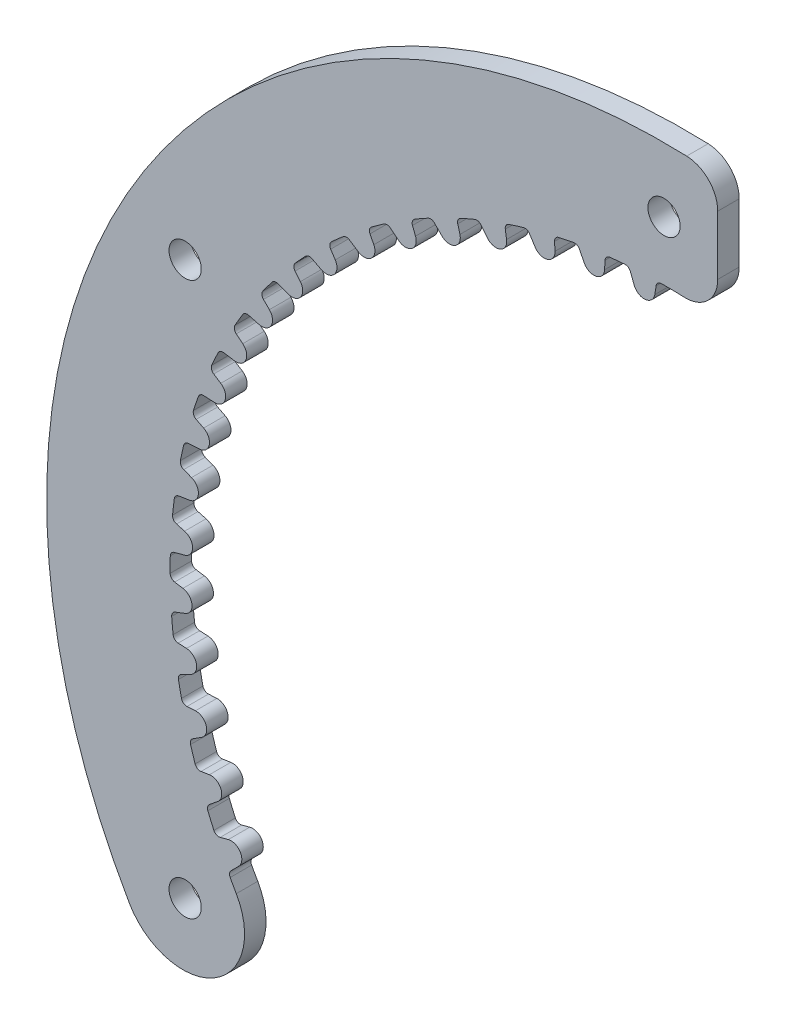
SolidWorks part; units mm, degrees
ref_plane "前视基准面" through (0, 0, 0) normal (0, 0, 1) x (1, 0, 0)
ref_plane "上视基准面" through (0, 0, 0) normal (0, 1, 0) x (1, 0, 0)
ref_plane "右视基准面" through (0, 0, 0) normal (1, 0, 0) x (0, 0, -1)
sketch "草图1" plane through (0, 0, 0) normal (0, 0, 1) x (1, 0, 0)
  line L6 (6.1601, 44.3885) -> (6.4016, 45.1318) [skipped]
  line L7 (0, 57.5) -> (6, 67.8923)
  line L10 (16.9119, 61.5923) -> (6.9151, 45.4773)
  line L11 (4.2309, 44.4896) -> (4.0233, 45.4665) [skipped]
  line L12 (3.8285, 44.65) -> (4.0308, 45.405)
  line L13 (1.8967, 44.65) -> (1.6382, 45.6147)
  line L14 (8.4748, 44.0052) -> (8.7549, 44.7349) [skipped]
  line L15 (6.5535, 44.2072) -> (6.3973, 45.1936) [skipped]
  line L16 (10.7662, 43.5014) -> (11.0841, 44.2154) [skipped]
  line L17 (8.8582, 43.8036) -> (8.7538, 44.7969) [skipped]
  line L164 (-37.109, -25.1238) -> (-37.823, -25.4417) [skipped]
  line L165 (-35.8932, -26.6252) -> (-36.4803, -27.4332) [skipped]
  line L166 (-38.373, -23.1473) -> (-39.1026, -23.4274) [skipped]
  line L167 (-37.2375, -24.7102) -> (-37.866, -25.4863) [skipped]
  line L168 (-39.5318, -21.1073) -> (-40.2752, -21.3488) [skipped]
  line L169 (-38.4797, -22.7274) -> (-39.148, -23.4697) [skipped]
  line L170 (-40.5823, -19.0094) -> (-41.3373, -19.2117)
  line L171 (-39.6164, -20.6824) -> (-40.3226, -21.3886)
  line L172 (-41.5216, -16.8594) -> (-42.2861, -17.0219) [skipped]
  line L173 (-40.6446, -18.5807) -> (-41.3868, -19.249) [skipped]
  line L174 (-42.347, -14.6633) -> (-43.119, -14.7855)
  line L175 (-41.5613, -16.4281) -> (-42.3375, -17.0566)
  line L176 (-43.0564, -12.4269) -> (-43.8337, -12.5086) [skipped]
  line L177 (-42.3641, -14.2304) -> (-43.1721, -14.8175) [skipped]
  line L178 (-43.6478, -10.1565) -> (-44.4283, -10.1974)
  line L179 (-43.0508, -11.9938) -> (-43.8884, -12.5377)
  line L180 (-44.1195, -7.8582) -> (-44.9011, -7.8582) [skipped]
  line L181 (-43.6195, -9.7242) -> (-44.4845, -10.2236) [skipped]
  line L182 (-44.4703, -5.5384) -> (-45.2508, -5.4975)
  line L183 (-44.0687, -7.428) -> (-44.9586, -7.8814)
  line L184 (-44.6992, -3.2034) -> (-45.4765, -3.1217) [skipped]
  line L185 (-44.397, -5.1115) -> (-45.3094, -5.5177) [skipped]
  line L186 (-44.8056, -0.8596) -> (-45.5776, -0.7374)
  line L187 (-44.6037, -2.7809) -> (-45.5361, -3.1388)
  line L188 (-44.7892, 1.4865) -> (-45.5537, 1.649) [skipped]
  line L189 (-44.6881, -0.4427) -> (-45.638, -0.7513) [skipped]
  line L190 (-44.65, 3.8285) -> (-45.405, 4.0308)
  line L191 (-44.65, 1.8967) -> (-45.6147, 1.6382)
  line L192 (-44.3885, 6.1601) -> (-45.1318, 6.4016) [skipped]
  line L193 (-44.4896, 4.2309) -> (-45.4665, 4.0233) [skipped]
  line L194 (-44.0052, 8.4748) -> (-44.7349, 8.7549)
  line L195 (-44.2072, 6.5535) -> (-45.1936, 6.3973)
  line L196 (-43.5014, 10.7662) -> (-44.2154, 11.0841) [skipped]
  line L197 (-43.8036, 8.8582) -> (-44.7969, 8.7538) [skipped]
  line L198 (-42.8783, 13.0282) -> (-43.5747, 13.383)
  line L199 (-43.28, 11.1385) -> (-44.2773, 11.0862)
  line L200 (-42.1377, 15.2544) -> (-42.8146, 15.6452) [skipped]
  line L201 (-42.6377, 13.3883) -> (-43.6365, 13.3883) [skipped]
  line L202 (-41.2816, 17.4388) -> (-41.9371, 17.8645)
  line L203 (-41.8786, 15.6015) -> (-42.876, 15.6538)
  line L204 (-40.3124, 19.5754) -> (-40.9447, 20.0348) [skipped]
  line L205 (-41.0047, 17.7719) -> (-41.9979, 17.8763) [skipped]
  line L206 (-39.2326, 21.6584) -> (-39.84, 22.1502)
  line L207 (-40.0184, 19.8935) -> (-41.0048, 20.0498)
  line L208 (-38.0454, 23.682) -> (-38.6262, 24.2049) [skipped]
  line L209 (-38.9224, 21.9607) -> (-39.8993, 22.1683) [skipped]
  line L210 (-36.7538, 25.6406) -> (-37.3064, 26.1933)
  line L211 (-37.7197, 23.9676) -> (-38.6844, 24.2261)
  line L212 (-35.3615, 27.529) -> (-35.8845, 28.1099) [skipped]
  line L213 (-36.4137, 25.9089) -> (-37.3635, 26.2175) [skipped]
  line L214 (-33.8723, 29.342) -> (-34.3641, 29.9494)
  line L215 (-35.0078, 27.7791) -> (-35.9402, 28.137)
  line L216 (-32.2902, 31.0745) -> (-32.7496, 31.7068) [skipped]
  line L217 (-33.506, 29.5732) -> (-34.4184, 29.9794) [skipped]
  line L218 (-30.6196, 32.7219) -> (-31.0453, 33.3773)
  line L219 (-31.9123, 31.2862) -> (-32.8022, 31.7396)
  line L220 (-28.8652, 34.2795) -> (-29.2559, 34.9564) [skipped]
  line L221 (-30.2312, 32.9135) -> (-31.0961, 33.4129) [skipped]
  line L222 (-27.0315, 35.7432) -> (-27.3864, 36.4396)
  line L223 (-28.4672, 34.4506) -> (-29.3048, 34.9945)
  line L224 (-25.1238, 37.109) -> (-25.4417, 37.823) [skipped]
  line L225 (-26.6252, 35.8932) -> (-27.4332, 36.4803) [skipped]
  line L226 (-23.1473, 38.373) -> (-23.4274, 39.1026)
  line L227 (-24.7102, 37.2375) -> (-25.4863, 37.866)
  line L228 (-21.1073, 39.5318) -> (-21.3488, 40.2752) [skipped]
  line L229 (-22.7274, 38.4797) -> (-23.4697, 39.148) [skipped]
  line L230 (-19.0094, 40.5823) -> (-19.2117, 41.3373)
  line L231 (-20.6824, 39.6164) -> (-21.3886, 40.3226)
  line L232 (-16.8594, 41.5216) -> (-17.0219, 42.2861) [skipped]
  line L233 (-18.5807, 40.6446) -> (-19.249, 41.3868) [skipped]
  line L234 (-14.6633, 42.347) -> (-14.7855, 43.119)
  line L235 (-16.4281, 41.5613) -> (-17.0566, 42.3375)
  line L236 (-12.4269, 43.0564) -> (-12.5086, 43.8337) [skipped]
  line L237 (-14.2304, 42.3641) -> (-14.8175, 43.1721) [skipped]
  line L238 (-10.1565, 43.6478) -> (-10.1974, 44.4283)
  line L239 (-11.9938, 43.0508) -> (-12.5377, 43.8884)
  line L240 (-7.8582, 44.1195) -> (-7.8582, 44.9011) [skipped]
  line L241 (-9.7242, 43.6195) -> (-10.2236, 44.4845) [skipped]
  line L242 (-5.5384, 44.4703) -> (-5.4975, 45.2508)
  line L243 (-7.428, 44.0687) -> (-7.8814, 44.9586)
  line L244 (-3.2034, 44.6992) -> (-3.1217, 45.4765) [skipped]
  line L245 (-5.1115, 44.397) -> (-5.5177, 45.3094) [skipped]
  line L246 (-0.8596, 44.8056) -> (-0.7374, 45.5776)
  line L247 (-2.7809, 44.6037) -> (-3.1388, 45.5361)
  line L248 (1.4865, 44.7892) -> (1.649, 45.5537) [skipped]
  line L249 (-0.4427, 44.6881) -> (-0.7513, 45.638) [skipped]
  line L250 (21.6584, 39.2326) -> (22.1502, 39.84) [skipped]
  line L251 (23.682, 38.0454) -> (24.2049, 38.6262) [skipped]
  line L252 (21.9607, 38.9224) -> (22.1683, 39.8993) [skipped]
  line L253 (25.6406, 36.7538) -> (26.1933, 37.3064) [skipped]
  line L254 (23.9676, 37.7197) -> (24.2261, 38.6844) [skipped]
  line L255 (27.529, 35.3615) -> (28.1099, 35.8845) [skipped]
  line L256 (25.9089, 36.4137) -> (26.2175, 37.3635) [skipped]
  line L257 (29.342, 33.8723) -> (29.9494, 34.3641) [skipped]
  line L258 (27.7791, 35.0078) -> (28.137, 35.9402) [skipped]
  line L259 (31.0745, 32.2902) -> (31.7068, 32.7496) [skipped]
  line L260 (29.5732, 33.506) -> (29.9794, 34.4184) [skipped]
  line L261 (32.7219, 30.6196) -> (33.3773, 31.0453) [skipped]
  line L262 (31.2862, 31.9123) -> (31.7396, 32.8022) [skipped]
  line L263 (34.2795, 28.8652) -> (34.9564, 29.2559) [skipped]
  line L264 (32.9135, 30.2312) -> (33.4129, 31.0961) [skipped]
  line L265 (35.7432, 27.0315) -> (36.4396, 27.3864) [skipped]
  line L266 (34.4506, 28.4672) -> (34.9945, 29.3048) [skipped]
  line L267 (37.109, 25.1238) -> (37.823, 25.4417) [skipped]
  line L268 (35.8932, 26.6252) -> (36.4803, 27.4332) [skipped]
  line L269 (38.373, 23.1473) -> (39.1026, 23.4274) [skipped]
  line L270 (37.2375, 24.7102) -> (37.866, 25.4863) [skipped]
  line L271 (39.5318, 21.1073) -> (40.2752, 21.3488) [skipped]
  line L272 (38.4797, 22.7274) -> (39.148, 23.4697) [skipped]
  line L273 (40.5823, 19.0094) -> (41.3373, 19.2117) [skipped]
  line L274 (39.6164, 20.6824) -> (40.3226, 21.3886) [skipped]
  line L275 (41.5216, 16.8594) -> (42.2861, 17.0219) [skipped]
  line L276 (40.6446, 18.5807) -> (41.3868, 19.249) [skipped]
  line L277 (42.347, 14.6633) -> (43.119, 14.7855) [skipped]
  line L278 (41.5613, 16.4281) -> (42.3375, 17.0566) [skipped]
  line L279 (43.0564, 12.4269) -> (43.8337, 12.5086) [skipped]
  line L280 (42.3641, 14.2304) -> (43.1721, 14.8175) [skipped]
  line L281 (43.6478, 10.1565) -> (44.4283, 10.1974) [skipped]
  line L282 (43.0508, 11.9938) -> (43.8884, 12.5377) [skipped]
  line L283 (44.1195, 7.8582) -> (44.9011, 7.8582) [skipped]
  line L284 (43.6195, 9.7242) -> (44.4845, 10.2236) [skipped]
  line L285 (44.4703, 5.5384) -> (45.2508, 5.4975) [skipped]
  line L286 (44.0687, 7.428) -> (44.9586, 7.8814) [skipped]
  line L287 (44.6992, 3.2034) -> (45.4765, 3.1217) [skipped]
  line L288 (44.397, 5.1115) -> (45.3094, 5.5177) [skipped]
  line L289 (44.8056, 0.8596) -> (45.5776, 0.7374) [skipped]
  line L290 (44.6037, 2.7809) -> (45.5361, 3.1388) [skipped]
  line L291 (44.7892, -1.4865) -> (45.5537, -1.649) [skipped]
  line L292 (44.6881, 0.4427) -> (45.638, 0.7513) [skipped]
  line L293 (44.65, -3.8285) -> (45.405, -4.0308) [skipped]
  line L294 (44.65, -1.8967) -> (45.6147, -1.6382) [skipped]
  line L295 (44.3885, -6.1601) -> (45.1318, -6.4016) [skipped]
  line L296 (44.4896, -4.2309) -> (45.4665, -4.0233) [skipped]
  line L297 (44.0052, -8.4748) -> (44.7349, -8.7549) [skipped]
  line L298 (44.2072, -6.5535) -> (45.1936, -6.3973) [skipped]
  line L299 (43.5014, -10.7662) -> (44.2154, -11.0841) [skipped]
  line L300 (43.8036, -8.8582) -> (44.7969, -8.7538) [skipped]
  line L301 (42.8783, -13.0282) -> (43.5747, -13.383) [skipped]
  line L302 (43.28, -11.1385) -> (44.2773, -11.0862) [skipped]
  line L303 (42.1377, -15.2544) -> (42.8146, -15.6452) [skipped]
  line L304 (42.6377, -13.3883) -> (43.6365, -13.3883) [skipped]
  line L305 (41.2816, -17.4388) -> (41.9371, -17.8645) [skipped]
  line L306 (41.8786, -15.6015) -> (42.876, -15.6538) [skipped]
  line L307 (40.3124, -19.5754) -> (40.9447, -20.0348) [skipped]
  line L308 (41.0047, -17.7719) -> (41.9979, -17.8763) [skipped]
  line L309 (39.2326, -21.6584) -> (39.84, -22.1502) [skipped]
  line L310 (40.0184, -19.8935) -> (41.0048, -20.0498) [skipped]
  line L311 (38.0454, -23.682) -> (38.6262, -24.2049) [skipped]
  line L312 (38.9224, -21.9607) -> (39.8993, -22.1683) [skipped]
  line L313 (36.7538, -25.6406) -> (37.3064, -26.1933) [skipped]
  line L314 (37.7197, -23.9676) -> (38.6844, -24.2261) [skipped]
  line L315 (35.3615, -27.529) -> (35.8845, -28.1099) [skipped]
  line L316 (36.4137, -25.9089) -> (37.3635, -26.2175) [skipped]
  line L317 (33.8723, -29.342) -> (34.3641, -29.9494) [skipped]
  line L318 (35.0078, -27.7791) -> (35.9402, -28.137) [skipped]
  line L319 (32.2902, -31.0745) -> (32.7496, -31.7068) [skipped]
  line L320 (33.506, -29.5732) -> (34.4184, -29.9794) [skipped]
  line L321 (30.6196, -32.7219) -> (31.0453, -33.3773) [skipped]
  line L322 (31.9123, -31.2862) -> (32.8022, -31.7396) [skipped]
  line L323 (28.8652, -34.2795) -> (29.2559, -34.9564) [skipped]
  line L324 (30.2312, -32.9135) -> (31.0961, -33.4129) [skipped]
  line L325 (27.0315, -35.7432) -> (27.3864, -36.4396) [skipped]
  line L326 (28.4672, -34.4506) -> (29.3048, -34.9945) [skipped]
  line L327 (25.1238, -37.109) -> (25.4417, -37.823) [skipped]
  line L328 (26.6252, -35.8932) -> (27.4332, -36.4803) [skipped]
  line L329 (23.1473, -38.373) -> (23.4274, -39.1026) [skipped]
  line L330 (24.7102, -37.2375) -> (25.4863, -37.866) [skipped]
  line L331 (21.1073, -39.5318) -> (21.3488, -40.2752) [skipped]
  line L332 (22.7274, -38.4797) -> (23.4697, -39.148) [skipped]
  line L333 (19.0094, -40.5823) -> (19.2117, -41.3373) [skipped]
  line L334 (20.6824, -39.6164) -> (21.3886, -40.3226) [skipped]
  line L335 (16.8594, -41.5216) -> (17.0219, -42.2861) [skipped]
  line L336 (18.5807, -40.6446) -> (19.249, -41.3868) [skipped]
  line L337 (14.6633, -42.347) -> (14.7855, -43.119) [skipped]
  line L338 (16.4281, -41.5613) -> (17.0566, -42.3375) [skipped]
  line L339 (12.4269, -43.0564) -> (12.5086, -43.8337) [skipped]
  line L340 (14.2304, -42.3641) -> (14.8175, -43.1721) [skipped]
  line L341 (10.1565, -43.6478) -> (10.1974, -44.4283) [skipped]
  line L342 (11.9938, -43.0508) -> (12.5377, -43.8884) [skipped]
  line L343 (7.8582, -44.1195) -> (7.8582, -44.9011) [skipped]
  line L344 (9.7242, -43.6195) -> (10.2236, -44.4845) [skipped]
  line L345 (5.5384, -44.4703) -> (5.4975, -45.2508) [skipped]
  line L346 (7.428, -44.0687) -> (7.8814, -44.9586) [skipped]
  line L347 (3.2034, -44.6992) -> (3.1217, -45.4765) [skipped]
  line L348 (5.1115, -44.397) -> (5.5177, -45.3094) [skipped]
  line L349 (0.8596, -44.8056) -> (0.7374, -45.5776) [skipped]
  line L350 (2.7809, -44.6037) -> (3.1388, -45.5361) [skipped]
  line L351 (-1.4865, -44.7892) -> (-1.649, -45.5537) [skipped]
  line L352 (0.4427, -44.6881) -> (0.7513, -45.638) [skipped]
  line L353 (-3.8285, -44.65) -> (-4.0308, -45.405) [skipped]
  line L354 (-1.8967, -44.65) -> (-1.6382, -45.6147) [skipped]
  line L355 (-6.1601, -44.3885) -> (-6.4016, -45.1318) [skipped]
  line L356 (-4.2309, -44.4896) -> (-4.0233, -45.4665) [skipped]
  line L357 (-8.4748, -44.0052) -> (-8.7549, -44.7349) [skipped]
  line L358 (-6.5535, -44.2072) -> (-6.3973, -45.1936) [skipped]
  line L359 (-10.7662, -43.5014) -> (-11.0841, -44.2154) [skipped]
  line L360 (-8.8582, -43.8036) -> (-8.7538, -44.7969) [skipped]
  line L361 (-13.0282, -42.8783) -> (-13.383, -43.5747) [skipped]
  line L362 (-11.1385, -43.28) -> (-11.0862, -44.2773) [skipped]
  line L363 (-15.2544, -42.1377) -> (-15.6452, -42.8146) [skipped]
  line L364 (-13.3883, -42.6377) -> (-13.3883, -43.6365) [skipped]
  line L365 (-17.4388, -41.2816) -> (-17.8645, -41.9371) [skipped]
  line L366 (-15.6015, -41.8786) -> (-15.6538, -42.876) [skipped]
  line L367 (-19.5754, -40.3124) -> (-20.0348, -40.9447) [skipped]
  line L368 (-17.7719, -41.0047) -> (-17.8763, -41.9979) [skipped]
  line L369 (-21.6584, -39.2326) -> (-22.1502, -39.84) [skipped]
  line L370 (-19.8935, -40.0184) -> (-20.0498, -41.0048) [skipped]
  line L371 (-23.682, -38.0454) -> (-24.2049, -38.6262) [skipped]
  line L372 (-21.9607, -38.9224) -> (-22.1683, -39.8993) [skipped]
  line L373 (-25.6406, -36.7538) -> (-26.1933, -37.3064) [skipped]
  line L374 (-23.9676, -37.7197) -> (-24.2261, -38.6844) [skipped]
  line L375 (-27.529, -35.3615) -> (-28.1099, -35.8845) [skipped]
  line L376 (-25.9089, -36.4137) -> (-26.2175, -37.3635) [skipped]
  line L377 (-29.342, -33.8723) -> (-29.9494, -34.3641) [skipped]
  line L378 (-27.7791, -35.0078) -> (-28.137, -35.9402) [skipped]
  line L379 (-31.0745, -32.2902) -> (-31.7068, -32.7496) [skipped]
  line L380 (-29.5732, -33.506) -> (-29.9794, -34.4184) [skipped]
  line L381 (-32.7219, -30.6196) -> (-33.3773, -31.0453) [skipped]
  line L382 (-31.2862, -31.9123) -> (-31.7396, -32.8022) [skipped]
  line L383 (-34.2795, -28.8652) -> (-34.9564, -29.2559) [skipped]
  line L384 (-32.9135, -30.2312) -> (-33.4129, -31.0961) [skipped]
  line L385 (-35.7432, -27.0315) -> (-36.4396, -27.3864) [skipped]
  line L386 (-34.4506, -28.4672) -> (-34.9945, -29.3048) [skipped]
  line L387 (13.0282, 42.8783) -> (13.383, 43.5747) [skipped]
  line L388 (11.1385, 43.28) -> (11.0862, 44.2773) [skipped]
  line L389 (15.2544, 42.1377) -> (15.6452, 42.8146) [skipped]
  line L390 (13.3883, 42.6377) -> (13.3883, 43.6365) [skipped]
  line L391 (17.4388, 41.2816) -> (17.8645, 41.9371) [skipped]
  line L392 (15.6015, 41.8786) -> (15.6538, 42.876) [skipped]
  line L393 (19.5754, 40.3124) -> (20.0348, 40.9447) [skipped]
  line L394 (17.7719, 41.0047) -> (17.8763, 41.9979) [skipped]
  line L395 (19.8935, 40.0184) -> (20.0498, 41.0048) [skipped]
  arc A0 (0, 57.5) -> (-49.7965, -28.75) centre (0, 0) ccw
  arc A2 (6.9151, 45.4773) -> (4.5634, 45.7731) centre (0, 0) ccw
  arc A3 (-49.7965, -28.75) -> (-39.8372, -23) centre (-44.8168, -25.875) ccw
  circle A4 centre (15.656, 72.0169) radius 3
  arc A5 (16.9119, 61.5923) -> (6, 67.8923) centre (15.656, 72.0169) ccw
  arc A12 (4.5634, 45.7731) -> (4.0308, 45.405) centre (4.5138, 45.2756) ccw
  arc A90 (1.8967, 44.65) -> (3.8285, 44.65) centre (2.8626, 44.9089) ccw
  arc A140 (1.6382, 45.6147) -> (1.1679, 45.9852) centre (1.1552, 45.4853) ccw
  arc A141 (4.2309, 44.4896) -> (6.1601, 44.3885) centre (5.209, 44.6975) ccw [skipped]
  arc A142 (6.9527, 45.4715) -> (6.4016, 45.1318) centre (6.8771, 44.9773) ccw [skipped]
  arc A143 (4.0233, 45.4665) -> (3.573, 45.861) centre (3.5342, 45.3625) ccw [skipped]
  arc A144 (6.5535, 44.2072) -> (8.4748, 44.0052) centre (7.5412, 44.3636) ccw [skipped]
  arc A145 (9.323, 45.0453) -> (8.7549, 44.7349) centre (9.2216, 44.5557) ccw [skipped]
  arc A146 (6.3973, 45.1936) -> (5.9683, 45.6112) centre (5.9034, 45.1154) ccw [skipped]
  arc A147 (8.8582, 43.8036) -> (10.7662, 43.5014) centre (9.8527, 43.9081) ccw [skipped]
  arc A148 (11.6677, 44.4957) -> (11.0841, 44.2154) centre (11.5409, 44.012) ccw [skipped]
  arc A149 (8.7538, 44.7969) -> (8.3472, 45.2363) centre (8.2565, 44.7446) ccw [skipped]
  arc A150 (-3.6452, 45.8553) -> (-5.0531, 45.7216) centre (0, 0) ccw
  arc A151 (1.1679, 45.9852) -> (-0.2462, 45.9993) centre (0, 0) ccw
  arc A152 (-8.4184, 45.2231) -> (-9.8046, 44.943) centre (0, 0) ccw
  arc A153 (-13.0994, 44.0954) -> (-14.4487, 43.6719) centre (0, 0) ccw
  arc A154 (-17.6369, 42.4846) -> (-18.9345, 41.9224) centre (0, 0) ccw
  arc A155 (-21.9811, 40.4083) -> (-23.2129, 39.7135) centre (0, 0) ccw
  arc A156 (-26.0845, 37.8893) -> (-27.2369, 37.0695) centre (0, 0) ccw
  arc A157 (-29.9021, 34.9551) -> (-30.9625, 34.0194) centre (0, 0) ccw
  arc A158 (-33.3921, 31.638) -> (-34.3489, 30.5966) centre (0, 0) ccw
  arc A159 (-36.5163, 27.9743) -> (-37.359, 26.8386) centre (0, 0) ccw
  arc A160 (-39.2404, 24.004) -> (-39.9597, 22.7865) centre (0, 0) ccw
  arc A161 (-41.5345, 19.7708) -> (-42.1226, 18.4847) centre (0, 0) ccw
  arc A162 (-43.3736, 15.321) -> (-43.8241, 13.9804) centre (0, 0) ccw
  arc A163 (-44.7375, 10.7033) -> (-45.0453, 9.323) centre (0, 0) ccw
  arc A164 (-45.6112, 5.9683) -> (-45.7731, 4.5634) centre (0, 0) ccw
  arc A165 (-45.9852, 1.1679) -> (-45.9993, -0.2462) centre (0, 0) ccw
  arc A166 (-45.8553, -3.6452) -> (-45.7216, -5.0531) centre (0, 0) ccw
  arc A167 (-45.2231, -8.4184) -> (-44.943, -9.8046) centre (0, 0) ccw
  arc A168 (-44.0954, -13.0994) -> (-43.6719, -14.4487) centre (0, 0) ccw
  arc A169 (-42.4846, -17.6369) -> (-41.9224, -18.9345) centre (0, 0) ccw
  arc A170 (-40.4083, -21.9811) -> (-39.8372, -23) centre (0, 0) ccw
  arc A369 (-35.8932, -26.6252) -> (-37.109, -25.1238) centre (-36.7022, -26.0374) ccw [skipped]
  arc A370 (-38.4442, -25.2595) -> (-37.823, -25.4417) centre (-38.0263, -24.985) ccw [skipped]
  arc A371 (-36.4803, -27.4332) -> (-36.4722, -28.0317) centre (-36.0758, -27.7271) ccw [skipped]
  arc A372 (-37.2375, -24.7102) -> (-38.373, -23.1473) centre (-38.0146, -24.0809) ccw [skipped]
  arc A373 (-39.7135, -23.2129) -> (-39.1026, -23.4274) centre (-39.2818, -22.9606) ccw [skipped]
  arc A374 (-37.866, -25.4863) -> (-37.8893, -26.0845) centre (-37.4774, -25.801) ccw [skipped]
  arc A375 (-38.4797, -22.7274) -> (-39.5318, -21.1073) centre (-39.2228, -22.0583) ccw [skipped]
  arc A376 (-40.8739, -21.1026) -> (-40.2752, -21.3488) centre (-40.4297, -20.8732) ccw [skipped]
  arc A377 (-39.148, -23.4697) -> (-39.2025, -24.0658) centre (-38.7764, -23.8042) ccw [skipped]
  arc A378 (-39.6164, -20.6824) -> (-40.5823, -19.0094) centre (-40.3235, -19.9753) ccw
  arc A379 (-41.9224, -18.9345) -> (-41.3373, -19.2117) centre (-41.4667, -18.7287) ccw
  arc A380 (-40.3226, -21.3886) -> (-40.4083, -21.9811) centre (-39.9691, -21.7422) ccw
  arc A381 (-40.6446, -18.5807) -> (-41.5216, -16.8594) centre (-41.3137, -17.8376) ccw [skipped]
  arc A382 (-42.8559, -16.7145) -> (-42.2861, -17.0219) centre (-42.39, -16.5329) ccw [skipped]
  arc A383 (-41.3868, -19.249) -> (-41.5033, -19.8362) centre (-41.0522, -19.6206) ccw [skipped]
  arc A384 (-41.5613, -16.4281) -> (-42.347, -14.6633) centre (-42.1906, -15.6509) ccw
  arc A385 (-43.6719, -14.4487) -> (-43.119, -14.7855) centre (-43.1972, -14.2917) ccw
  arc A386 (-42.3375, -17.0566) -> (-42.4846, -17.6369) centre (-42.0228, -17.4452) ccw
  arc A387 (-42.3641, -14.2304) -> (-43.0564, -12.4269) centre (-42.9519, -13.4214) ccw [skipped]
  arc A388 (-44.3682, -12.1433) -> (-43.8337, -12.5086) centre (-43.886, -12.0113) ccw [skipped]
  arc A389 (-43.1721, -14.8175) -> (-43.3494, -15.3892) centre (-42.8782, -15.222) ccw [skipped]
  arc A390 (-43.0508, -11.9938) -> (-43.6478, -10.1565) centre (-43.5955, -11.1551) ccw
  arc A391 (-44.943, -9.8046) -> (-44.4283, -10.1974) centre (-44.4544, -9.698) ccw
  arc A392 (-43.8884, -12.5377) -> (-44.0954, -13.0994) centre (-43.6161, -12.957) ccw
  arc A393 (-43.6195, -9.7242) -> (-44.1195, -7.8582) centre (-44.1195, -8.8582) ccw [skipped]
  arc A394 (-45.3945, -7.439) -> (-44.9011, -7.8582) centre (-44.9011, -7.3582) ccw [skipped]
  arc A395 (-44.4845, -10.2236) -> (-44.7205, -10.7737) centre (-44.2345, -10.6566) ccw [skipped]
  arc A396 (-44.0687, -7.428) -> (-44.4703, -5.5384) centre (-44.5227, -6.537) ccw
  arc A397 (-45.7216, -5.0531) -> (-45.2508, -5.4975) centre (-45.2246, -4.9982) ccw
  arc A398 (-44.9586, -7.8814) -> (-45.2231, -8.4184) centre (-44.7316, -8.3269) ccw
  arc A399 (-44.397, -5.1115) -> (-44.6992, -3.2034) centre (-44.8038, -4.1979) ccw [skipped]
  arc A400 (-45.9234, -2.6533) -> (-45.4765, -3.1217) centre (-45.4242, -2.6244) ccw [skipped]
  arc A401 (-45.3094, -5.5177) -> (-45.6017, -6.0401) centre (-45.1061, -5.9745) ccw [skipped]
  arc A402 (-44.6037, -2.7809) -> (-44.8056, -0.8596) centre (-44.9621, -1.8473) ccw
  arc A403 (-45.9993, -0.2462) -> (-45.5776, -0.7374) centre (-45.4993, -0.2435) ccw
  arc A404 (-45.5361, -3.1388) -> (-45.8553, -3.6452) centre (-45.3569, -3.6056) ccw
  arc A405 (-44.6881, -0.4427) -> (-44.7892, 1.4865) centre (-44.9971, 0.5084) ccw [skipped]
  arc A406 (-45.9492, 2.1616) -> (-45.5537, 1.649) centre (-45.4497, 2.1381) ccw [skipped]
  arc A407 (-45.638, -0.7513) -> (-45.9833, -1.2403) centre (-45.4835, -1.2269) ccw [skipped]
  arc A408 (-44.65, 1.8967) -> (-44.65, 3.8285) centre (-44.9089, 2.8626) ccw
  arc A409 (-45.7731, 4.5634) -> (-45.405, 4.0308) centre (-45.2756, 4.5138) ccw
  arc A410 (-45.6147, 1.6382) -> (-45.9852, 1.1679) centre (-45.4853, 1.1552) ccw
  arc A411 (-44.4896, 4.2309) -> (-44.3885, 6.1601) centre (-44.6975, 5.209) ccw [skipped]
  arc A412 (-45.4715, 6.9527) -> (-45.1318, 6.4016) centre (-44.9773, 6.8771) ccw [skipped]
  arc A413 (-45.4665, 4.0233) -> (-45.861, 3.573) centre (-45.3625, 3.5342) ccw [skipped]
  arc A414 (-44.2072, 6.5535) -> (-44.0052, 8.4748) centre (-44.3636, 7.5412) ccw
  arc A415 (-45.0453, 9.323) -> (-44.7349, 8.7549) centre (-44.5557, 9.2216) ccw
  arc A416 (-45.1936, 6.3973) -> (-45.6112, 5.9683) centre (-45.1154, 5.9034) ccw
  arc A417 (-43.8036, 8.8582) -> (-43.5014, 10.7662) centre (-43.9081, 9.8527) ccw [skipped]
  arc A418 (-44.4957, 11.6677) -> (-44.2154, 11.0841) centre (-44.012, 11.5409) ccw [skipped]
  arc A419 (-44.7969, 8.7538) -> (-45.2363, 8.3472) centre (-44.7446, 8.2565) ccw [skipped]
  arc A420 (-43.28, 11.1385) -> (-42.8783, 13.0282) centre (-43.3323, 12.1371) ccw
  arc A421 (-43.8241, 13.9804) -> (-43.5747, 13.383) centre (-43.3477, 13.8285) ccw
  arc A422 (-44.2773, 11.0862) -> (-44.7375, 10.7033) centre (-44.2512, 10.5869) ccw
  arc A423 (-42.6377, 13.3883) -> (-42.1377, 15.2544) centre (-42.6377, 14.3883) ccw [skipped]
  arc A424 (-43.0323, 16.2548) -> (-42.8146, 15.6452) centre (-42.5646, 16.0782) ccw [skipped]
  arc A425 (-43.6365, 13.3883) -> (-44.116, 13.03) centre (-43.6365, 12.8883) ccw [skipped]
  arc A426 (-41.8786, 15.6015) -> (-41.2816, 17.4388) centre (-41.8263, 16.6001) ccw
  arc A427 (-42.1226, 18.4847) -> (-41.9371, 17.8645) centre (-41.6648, 18.2838) ccw
  arc A428 (-42.876, 15.6538) -> (-43.3736, 15.321) centre (-42.9021, 15.1544) ccw
  arc A429 (-41.0047, 17.7719) -> (-40.3124, 19.5754) centre (-40.9002, 18.7664) ccw [skipped]
  arc A430 (-41.0975, 20.6639) -> (-40.9447, 20.0348) centre (-40.6508, 20.4393) ccw [skipped]
  arc A431 (-41.9979, 17.8763) -> (-42.5123, 17.57) centre (-42.0502, 17.379) ccw [skipped]
  arc A432 (-40.0184, 19.8935) -> (-39.2326, 21.6584) centre (-39.8619, 20.8812) ccw
  arc A433 (-39.9597, 22.7865) -> (-39.84, 22.1502) centre (-39.5254, 22.5388) ccw
  arc A434 (-41.0048, 20.0498) -> (-41.5345, 19.7708) centre (-41.083, 19.5559) ccw
  arc A435 (-38.9224, 21.9607) -> (-38.0454, 23.682) centre (-38.7145, 22.9388) ccw [skipped]
  arc A436 (-38.7124, 24.8466) -> (-38.6262, 24.2049) centre (-38.2916, 24.5765) ccw [skipped]
  arc A437 (-39.8993, 22.1683) -> (-40.4429, 21.9175) centre (-40.0033, 21.6792) ccw [skipped]
  arc A438 (-37.7197, 23.9676) -> (-36.7538, 25.6406) centre (-37.4609, 24.9335) ccw
  arc A439 (-37.359, 26.8386) -> (-37.3064, 26.1933) centre (-36.9529, 26.5468) ccw
  arc A440 (-38.6844, 24.2261) -> (-39.2404, 24.004) centre (-38.8138, 23.7431) ccw
  arc A441 (-36.4137, 25.9089) -> (-35.3615, 27.529) centre (-36.1046, 26.8599) ccw [skipped]
  arc A442 (-35.9031, 28.757) -> (-35.8845, 28.1099) centre (-35.5129, 28.4444) ccw [skipped]
  arc A443 (-37.3635, 26.2175) -> (-37.9303, 26.0248) centre (-37.518, 25.742) ccw [skipped]
  arc A444 (-35.0078, 27.7791) -> (-33.8723, 29.342) centre (-34.6494, 28.7127) ccw
  arc A445 (-34.3489, 30.5966) -> (-34.3641, 29.9494) centre (-33.9756, 30.264) ccw
  arc A446 (-35.9402, 28.137) -> (-36.5163, 27.9743) centre (-36.1194, 27.6702) ccw
  arc A447 (-33.506, 29.5732) -> (-32.2902, 31.0745) centre (-33.0992, 30.4867) ccw [skipped]
  arc A448 (-32.7005, 32.3524) -> (-32.7496, 31.7068) centre (-32.3451, 32.0007) ccw [skipped]
  arc A449 (-34.4184, 29.9794) -> (-35.0022, 29.8471) centre (-34.6217, 29.5226) ccw [skipped]
  arc A450 (-31.9123, 31.2862) -> (-30.6196, 32.7219) centre (-31.4583, 32.1772) ccw
  arc A451 (-30.9625, 34.0194) -> (-31.0453, 33.3773) centre (-30.626, 33.6497) ccw
  arc A452 (-32.8022, 31.7396) -> (-33.3921, 31.638) centre (-33.0292, 31.2941) ccw
  arc A453 (-30.2312, 32.9135) -> (-28.8652, 34.2795) centre (-29.7312, 33.7795) ccw [skipped]
  arc A454 (-29.1397, 35.5933) -> (-29.2559, 34.9564) centre (-28.8229, 35.2064) ccw [skipped]
  arc A455 (-31.0961, 33.4129) -> (-31.6906, 33.3423) centre (-31.3461, 32.9799) ccw [skipped]
  arc A456 (-28.4672, 34.4506) -> (-27.0315, 35.7432) centre (-27.9225, 35.2893) ccw
  arc A457 (-27.2369, 37.0695) -> (-27.3864, 36.4396) centre (-26.9409, 36.6666) ccw
  arc A458 (-29.3048, 34.9945) -> (-29.9021, 34.9551) centre (-29.5771, 34.5752) ccw
  arc A459 (-26.6252, 35.8932) -> (-25.1238, 37.109) centre (-26.0374, 36.7022) ccw [skipped]
  arc A460 (-25.2595, 38.4442) -> (-25.4417, 37.823) centre (-24.985, 38.0263) ccw [skipped]
  arc A461 (-27.4332, 36.4803) -> (-28.0317, 36.4722) centre (-27.7271, 36.0758) ccw [skipped]
  arc A462 (-24.7102, 37.2375) -> (-23.1473, 38.373) centre (-24.0809, 38.0146) ccw
  arc A463 (-23.2129, 39.7135) -> (-23.4274, 39.1026) centre (-22.9606, 39.2818) ccw
  arc A464 (-25.4863, 37.866) -> (-26.0845, 37.8893) centre (-25.801, 37.4774) ccw
  arc A465 (-22.7274, 38.4797) -> (-21.1073, 39.5318) centre (-22.0583, 39.2228) ccw [skipped]
  arc A466 (-21.1026, 40.8739) -> (-21.3488, 40.2752) centre (-20.8732, 40.4297) ccw [skipped]
  arc A467 (-23.4697, 39.148) -> (-24.0658, 39.2025) centre (-23.8042, 38.7764) ccw [skipped]
  arc A468 (-20.6824, 39.6164) -> (-19.0094, 40.5823) centre (-19.9753, 40.3235) ccw
  arc A469 (-18.9345, 41.9224) -> (-19.2117, 41.3373) centre (-18.7287, 41.4667) ccw
  arc A470 (-21.3886, 40.3226) -> (-21.9811, 40.4083) centre (-21.7422, 39.9691) ccw
  arc A471 (-18.5807, 40.6446) -> (-16.8594, 41.5216) centre (-17.8376, 41.3137) ccw [skipped]
  arc A472 (-16.7145, 42.8559) -> (-17.0219, 42.2861) centre (-16.5329, 42.39) ccw [skipped]
  arc A473 (-19.249, 41.3868) -> (-19.8362, 41.5033) centre (-19.6206, 41.0522) ccw [skipped]
  arc A474 (-16.4281, 41.5613) -> (-14.6633, 42.347) centre (-15.6509, 42.1906) ccw
  arc A475 (-14.4487, 43.6719) -> (-14.7855, 43.119) centre (-14.2917, 43.1972) ccw
  arc A476 (-17.0566, 42.3375) -> (-17.6369, 42.4846) centre (-17.4452, 42.0228) ccw
  arc A477 (-14.2304, 42.3641) -> (-12.4269, 43.0564) centre (-13.4214, 42.9519) ccw [skipped]
  arc A478 (-12.1433, 44.3682) -> (-12.5086, 43.8337) centre (-12.0113, 43.886) ccw [skipped]
  arc A479 (-14.8175, 43.1721) -> (-15.3892, 43.3494) centre (-15.222, 42.8782) ccw [skipped]
  arc A480 (-11.9938, 43.0508) -> (-10.1565, 43.6478) centre (-11.1551, 43.5955) ccw
  arc A481 (-9.8046, 44.943) -> (-10.1974, 44.4283) centre (-9.698, 44.4544) ccw
  arc A482 (-12.5377, 43.8884) -> (-13.0994, 44.0954) centre (-12.957, 43.6161) ccw
  arc A483 (-9.7242, 43.6195) -> (-7.8582, 44.1195) centre (-8.8582, 44.1195) ccw [skipped]
  arc A484 (-7.439, 45.3945) -> (-7.8582, 44.9011) centre (-7.3582, 44.9011) ccw [skipped]
  arc A485 (-10.2236, 44.4845) -> (-10.7737, 44.7205) centre (-10.6566, 44.2345) ccw [skipped]
  arc A486 (-7.428, 44.0687) -> (-5.5384, 44.4703) centre (-6.537, 44.5227) ccw
  arc A487 (-5.0531, 45.7216) -> (-5.4975, 45.2508) centre (-4.9982, 45.2246) ccw
  arc A488 (-7.8814, 44.9586) -> (-8.4184, 45.2231) centre (-8.3269, 44.7316) ccw
  arc A489 (-5.1115, 44.397) -> (-3.2034, 44.6992) centre (-4.1979, 44.8038) ccw [skipped]
  arc A490 (-2.6533, 45.9234) -> (-3.1217, 45.4765) centre (-2.6244, 45.4242) ccw [skipped]
  arc A491 (-5.5177, 45.3094) -> (-6.0401, 45.6017) centre (-5.9745, 45.1061) ccw [skipped]
  arc A492 (-2.7809, 44.6037) -> (-0.8596, 44.8056) centre (-1.8473, 44.9621) ccw
  arc A493 (-0.2462, 45.9993) -> (-0.7374, 45.5776) centre (-0.2435, 45.4993) ccw
  arc A494 (-3.1388, 45.5361) -> (-3.6452, 45.8553) centre (-3.6056, 45.3569) ccw
  arc A495 (-0.4427, 44.6881) -> (1.4865, 44.7892) centre (0.5084, 44.9971) ccw [skipped]
  arc A496 (2.1616, 45.9492) -> (1.649, 45.5537) centre (2.1381, 45.4497) ccw [skipped]
  arc A497 (-0.7513, 45.638) -> (-1.2403, 45.9833) centre (-1.2269, 45.4835) ccw [skipped]
  arc A498 (19.8935, 40.0184) -> (21.6584, 39.2326) centre (20.8812, 39.8619) ccw [skipped]
  arc A499 (22.7865, 39.9597) -> (22.1502, 39.84) centre (22.5388, 39.5254) ccw [skipped]
  arc A500 (21.9607, 38.9224) -> (23.682, 38.0454) centre (22.9388, 38.7145) ccw [skipped]
  arc A501 (24.8466, 38.7124) -> (24.2049, 38.6262) centre (24.5765, 38.2916) ccw [skipped]
  arc A502 (22.1683, 39.8993) -> (21.9175, 40.4429) centre (21.6792, 40.0033) ccw [skipped]
  arc A503 (23.9676, 37.7197) -> (25.6406, 36.7538) centre (24.9335, 37.4609) ccw [skipped]
  arc A504 (26.8386, 37.359) -> (26.1933, 37.3064) centre (26.5468, 36.9529) ccw [skipped]
  arc A505 (24.2261, 38.6844) -> (24.004, 39.2404) centre (23.7431, 38.8138) ccw [skipped]
  arc A506 (25.9089, 36.4137) -> (27.529, 35.3615) centre (26.8599, 36.1046) ccw [skipped]
  arc A507 (28.757, 35.9031) -> (28.1099, 35.8845) centre (28.4444, 35.5129) ccw [skipped]
  arc A508 (26.2175, 37.3635) -> (26.0248, 37.9303) centre (25.742, 37.518) ccw [skipped]
  arc A509 (27.7791, 35.0078) -> (29.342, 33.8723) centre (28.7127, 34.6494) ccw [skipped]
  arc A510 (30.5966, 34.3489) -> (29.9494, 34.3641) centre (30.264, 33.9756) ccw [skipped]
  arc A511 (28.137, 35.9402) -> (27.9743, 36.5163) centre (27.6702, 36.1194) ccw [skipped]
  arc A512 (29.5732, 33.506) -> (31.0745, 32.2902) centre (30.4867, 33.0992) ccw [skipped]
  arc A513 (32.3524, 32.7005) -> (31.7068, 32.7496) centre (32.0007, 32.3451) ccw [skipped]
  arc A514 (29.9794, 34.4184) -> (29.8471, 35.0022) centre (29.5226, 34.6217) ccw [skipped]
  arc A515 (31.2862, 31.9123) -> (32.7219, 30.6196) centre (32.1772, 31.4583) ccw [skipped]
  arc A516 (34.0194, 30.9625) -> (33.3773, 31.0453) centre (33.6497, 30.626) ccw [skipped]
  arc A517 (31.7396, 32.8022) -> (31.638, 33.3921) centre (31.2941, 33.0292) ccw [skipped]
  arc A518 (32.9135, 30.2312) -> (34.2795, 28.8652) centre (33.7795, 29.7312) ccw [skipped]
  arc A519 (35.5933, 29.1397) -> (34.9564, 29.2559) centre (35.2064, 28.8229) ccw [skipped]
  arc A520 (33.4129, 31.0961) -> (33.3423, 31.6906) centre (32.9799, 31.3461) ccw [skipped]
  arc A521 (34.4506, 28.4672) -> (35.7432, 27.0315) centre (35.2893, 27.9225) ccw [skipped]
  arc A522 (37.0695, 27.2369) -> (36.4396, 27.3864) centre (36.6666, 26.9409) ccw [skipped]
  arc A523 (34.9945, 29.3048) -> (34.9551, 29.9021) centre (34.5752, 29.5771) ccw [skipped]
  arc A524 (35.8932, 26.6252) -> (37.109, 25.1238) centre (36.7022, 26.0374) ccw [skipped]
  arc A525 (38.4442, 25.2595) -> (37.823, 25.4417) centre (38.0263, 24.985) ccw [skipped]
  arc A526 (36.4803, 27.4332) -> (36.4722, 28.0317) centre (36.0758, 27.7271) ccw [skipped]
  arc A527 (37.2375, 24.7102) -> (38.373, 23.1473) centre (38.0146, 24.0809) ccw [skipped]
  arc A528 (39.7135, 23.2129) -> (39.1026, 23.4274) centre (39.2818, 22.9606) ccw [skipped]
  arc A529 (37.866, 25.4863) -> (37.8893, 26.0845) centre (37.4774, 25.801) ccw [skipped]
  arc A530 (38.4797, 22.7274) -> (39.5318, 21.1073) centre (39.2228, 22.0583) ccw [skipped]
  arc A531 (40.8739, 21.1026) -> (40.2752, 21.3488) centre (40.4297, 20.8732) ccw [skipped]
  arc A532 (39.148, 23.4697) -> (39.2025, 24.0658) centre (38.7764, 23.8042) ccw [skipped]
  arc A533 (39.6164, 20.6824) -> (40.5823, 19.0094) centre (40.3235, 19.9753) ccw [skipped]
  arc A534 (41.9224, 18.9345) -> (41.3373, 19.2117) centre (41.4667, 18.7287) ccw [skipped]
  arc A535 (40.3226, 21.3886) -> (40.4083, 21.9811) centre (39.9691, 21.7422) ccw [skipped]
  arc A536 (40.6446, 18.5807) -> (41.5216, 16.8594) centre (41.3137, 17.8376) ccw [skipped]
  arc A537 (42.8559, 16.7145) -> (42.2861, 17.0219) centre (42.39, 16.5329) ccw [skipped]
  arc A538 (41.3868, 19.249) -> (41.5033, 19.8362) centre (41.0522, 19.6206) ccw [skipped]
  arc A539 (41.5613, 16.4281) -> (42.347, 14.6633) centre (42.1906, 15.6509) ccw [skipped]
  arc A540 (43.6719, 14.4487) -> (43.119, 14.7855) centre (43.1972, 14.2917) ccw [skipped]
  arc A541 (42.3375, 17.0566) -> (42.4846, 17.6369) centre (42.0228, 17.4452) ccw [skipped]
  arc A542 (42.3641, 14.2304) -> (43.0564, 12.4269) centre (42.9519, 13.4214) ccw [skipped]
  arc A543 (44.3682, 12.1433) -> (43.8337, 12.5086) centre (43.886, 12.0113) ccw [skipped]
  arc A544 (43.1721, 14.8175) -> (43.3494, 15.3892) centre (42.8782, 15.222) ccw [skipped]
  arc A545 (43.0508, 11.9938) -> (43.6478, 10.1565) centre (43.5955, 11.1551) ccw [skipped]
  arc A546 (44.943, 9.8046) -> (44.4283, 10.1974) centre (44.4544, 9.698) ccw [skipped]
  arc A547 (43.8884, 12.5377) -> (44.0954, 13.0994) centre (43.6161, 12.957) ccw [skipped]
  arc A548 (43.6195, 9.7242) -> (44.1195, 7.8582) centre (44.1195, 8.8582) ccw [skipped]
  arc A549 (45.3945, 7.439) -> (44.9011, 7.8582) centre (44.9011, 7.3582) ccw [skipped]
  arc A550 (44.4845, 10.2236) -> (44.7205, 10.7737) centre (44.2345, 10.6566) ccw [skipped]
  arc A551 (44.0687, 7.428) -> (44.4703, 5.5384) centre (44.5227, 6.537) ccw [skipped]
  arc A552 (45.7216, 5.0531) -> (45.2508, 5.4975) centre (45.2246, 4.9982) ccw [skipped]
  arc A553 (44.9586, 7.8814) -> (45.2231, 8.4184) centre (44.7316, 8.3269) ccw [skipped]
  arc A554 (44.397, 5.1115) -> (44.6992, 3.2034) centre (44.8038, 4.1979) ccw [skipped]
  arc A555 (45.9234, 2.6533) -> (45.4765, 3.1217) centre (45.4242, 2.6244) ccw [skipped]
  arc A556 (45.3094, 5.5177) -> (45.6017, 6.0401) centre (45.1061, 5.9745) ccw [skipped]
  arc A557 (44.6037, 2.7809) -> (44.8056, 0.8596) centre (44.9621, 1.8473) ccw [skipped]
  arc A558 (45.9993, 0.2462) -> (45.5776, 0.7374) centre (45.4993, 0.2435) ccw [skipped]
  arc A559 (45.5361, 3.1388) -> (45.8553, 3.6452) centre (45.3569, 3.6056) ccw [skipped]
  arc A560 (44.6881, 0.4427) -> (44.7892, -1.4865) centre (44.9971, -0.5084) ccw [skipped]
  arc A561 (45.9492, -2.1616) -> (45.5537, -1.649) centre (45.4497, -2.1381) ccw [skipped]
  arc A562 (45.638, 0.7513) -> (45.9833, 1.2403) centre (45.4835, 1.2269) ccw [skipped]
  arc A563 (44.65, -1.8967) -> (44.65, -3.8285) centre (44.9089, -2.8626) ccw [skipped]
  arc A564 (45.7731, -4.5634) -> (45.405, -4.0308) centre (45.2756, -4.5138) ccw [skipped]
  arc A565 (45.6147, -1.6382) -> (45.9852, -1.1679) centre (45.4853, -1.1552) ccw [skipped]
  arc A566 (44.4896, -4.2309) -> (44.3885, -6.1601) centre (44.6975, -5.209) ccw [skipped]
  arc A567 (45.4715, -6.9527) -> (45.1318, -6.4016) centre (44.9773, -6.8771) ccw [skipped]
  arc A568 (45.4665, -4.0233) -> (45.861, -3.573) centre (45.3625, -3.5342) ccw [skipped]
  arc A569 (44.2072, -6.5535) -> (44.0052, -8.4748) centre (44.3636, -7.5412) ccw [skipped]
  arc A570 (45.0453, -9.323) -> (44.7349, -8.7549) centre (44.5557, -9.2216) ccw [skipped]
  arc A571 (45.1936, -6.3973) -> (45.6112, -5.9683) centre (45.1154, -5.9034) ccw [skipped]
  arc A572 (43.8036, -8.8582) -> (43.5014, -10.7662) centre (43.9081, -9.8527) ccw [skipped]
  arc A573 (44.4957, -11.6677) -> (44.2154, -11.0841) centre (44.012, -11.5409) ccw [skipped]
  arc A574 (44.7969, -8.7538) -> (45.2363, -8.3472) centre (44.7446, -8.2565) ccw [skipped]
  arc A575 (43.28, -11.1385) -> (42.8783, -13.0282) centre (43.3323, -12.1371) ccw [skipped]
  arc A576 (43.8241, -13.9804) -> (43.5747, -13.383) centre (43.3477, -13.8285) ccw [skipped]
  arc A577 (44.2773, -11.0862) -> (44.7375, -10.7033) centre (44.2512, -10.5869) ccw [skipped]
  arc A578 (42.6377, -13.3883) -> (42.1377, -15.2544) centre (42.6377, -14.3883) ccw [skipped]
  arc A579 (43.0323, -16.2548) -> (42.8146, -15.6452) centre (42.5646, -16.0782) ccw [skipped]
  arc A580 (43.6365, -13.3883) -> (44.116, -13.03) centre (43.6365, -12.8883) ccw [skipped]
  arc A581 (41.8786, -15.6015) -> (41.2816, -17.4388) centre (41.8263, -16.6001) ccw [skipped]
  arc A582 (42.1226, -18.4847) -> (41.9371, -17.8645) centre (41.6648, -18.2838) ccw [skipped]
  arc A583 (42.876, -15.6538) -> (43.3736, -15.321) centre (42.9021, -15.1544) ccw [skipped]
  arc A584 (41.0047, -17.7719) -> (40.3124, -19.5754) centre (40.9002, -18.7664) ccw [skipped]
  arc A585 (41.0975, -20.6639) -> (40.9447, -20.0348) centre (40.6508, -20.4393) ccw [skipped]
  arc A586 (41.9979, -17.8763) -> (42.5123, -17.57) centre (42.0502, -17.379) ccw [skipped]
  arc A587 (40.0184, -19.8935) -> (39.2326, -21.6584) centre (39.8619, -20.8812) ccw [skipped]
  arc A588 (39.9597, -22.7865) -> (39.84, -22.1502) centre (39.5254, -22.5388) ccw [skipped]
  arc A589 (41.0048, -20.0498) -> (41.5345, -19.7708) centre (41.083, -19.5559) ccw [skipped]
  arc A590 (38.9224, -21.9607) -> (38.0454, -23.682) centre (38.7145, -22.9388) ccw [skipped]
  arc A591 (38.7124, -24.8466) -> (38.6262, -24.2049) centre (38.2916, -24.5765) ccw [skipped]
  arc A592 (39.8993, -22.1683) -> (40.4429, -21.9175) centre (40.0033, -21.6792) ccw [skipped]
  arc A593 (37.7197, -23.9676) -> (36.7538, -25.6406) centre (37.4609, -24.9335) ccw [skipped]
  arc A594 (37.359, -26.8386) -> (37.3064, -26.1933) centre (36.9529, -26.5468) ccw [skipped]
  arc A595 (38.6844, -24.2261) -> (39.2404, -24.004) centre (38.8138, -23.7431) ccw [skipped]
  arc A596 (36.4137, -25.9089) -> (35.3615, -27.529) centre (36.1046, -26.8599) ccw [skipped]
  arc A597 (35.9031, -28.757) -> (35.8845, -28.1099) centre (35.5129, -28.4444) ccw [skipped]
  arc A598 (37.3635, -26.2175) -> (37.9303, -26.0248) centre (37.518, -25.742) ccw [skipped]
  arc A599 (35.0078, -27.7791) -> (33.8723, -29.342) centre (34.6494, -28.7127) ccw [skipped]
  arc A600 (34.3489, -30.5966) -> (34.3641, -29.9494) centre (33.9756, -30.264) ccw [skipped]
  arc A601 (35.9402, -28.137) -> (36.5163, -27.9743) centre (36.1194, -27.6702) ccw [skipped]
  arc A602 (33.506, -29.5732) -> (32.2902, -31.0745) centre (33.0992, -30.4867) ccw [skipped]
  arc A603 (32.7005, -32.3524) -> (32.7496, -31.7068) centre (32.3451, -32.0007) ccw [skipped]
  arc A604 (34.4184, -29.9794) -> (35.0022, -29.8471) centre (34.6217, -29.5226) ccw [skipped]
  arc A605 (31.9123, -31.2862) -> (30.6196, -32.7219) centre (31.4583, -32.1772) ccw [skipped]
  arc A606 (30.9625, -34.0194) -> (31.0453, -33.3773) centre (30.626, -33.6497) ccw [skipped]
  arc A607 (32.8022, -31.7396) -> (33.3921, -31.638) centre (33.0292, -31.2941) ccw [skipped]
  arc A608 (30.2312, -32.9135) -> (28.8652, -34.2795) centre (29.7312, -33.7795) ccw [skipped]
  arc A609 (29.1397, -35.5933) -> (29.2559, -34.9564) centre (28.8229, -35.2064) ccw [skipped]
  arc A610 (31.0961, -33.4129) -> (31.6906, -33.3423) centre (31.3461, -32.9799) ccw [skipped]
  arc A611 (28.4672, -34.4506) -> (27.0315, -35.7432) centre (27.9225, -35.2893) ccw [skipped]
  arc A612 (27.2369, -37.0695) -> (27.3864, -36.4396) centre (26.9409, -36.6666) ccw [skipped]
  arc A613 (29.3048, -34.9945) -> (29.9021, -34.9551) centre (29.5771, -34.5752) ccw [skipped]
  arc A614 (26.6252, -35.8932) -> (25.1238, -37.109) centre (26.0374, -36.7022) ccw [skipped]
  arc A615 (25.2595, -38.4442) -> (25.4417, -37.823) centre (24.985, -38.0263) ccw [skipped]
  arc A616 (27.4332, -36.4803) -> (28.0317, -36.4722) centre (27.7271, -36.0758) ccw [skipped]
  arc A617 (24.7102, -37.2375) -> (23.1473, -38.373) centre (24.0809, -38.0146) ccw [skipped]
  arc A618 (23.2129, -39.7135) -> (23.4274, -39.1026) centre (22.9606, -39.2818) ccw [skipped]
  arc A619 (25.4863, -37.866) -> (26.0845, -37.8893) centre (25.801, -37.4774) ccw [skipped]
  arc A620 (22.7274, -38.4797) -> (21.1073, -39.5318) centre (22.0583, -39.2228) ccw [skipped]
  arc A621 (21.1026, -40.8739) -> (21.3488, -40.2752) centre (20.8732, -40.4297) ccw [skipped]
  arc A622 (23.4697, -39.148) -> (24.0658, -39.2025) centre (23.8042, -38.7764) ccw [skipped]
  arc A623 (20.6824, -39.6164) -> (19.0094, -40.5823) centre (19.9753, -40.3235) ccw [skipped]
  arc A624 (18.9345, -41.9224) -> (19.2117, -41.3373) centre (18.7287, -41.4667) ccw [skipped]
  arc A625 (21.3886, -40.3226) -> (21.9811, -40.4083) centre (21.7422, -39.9691) ccw [skipped]
  arc A626 (18.5807, -40.6446) -> (16.8594, -41.5216) centre (17.8376, -41.3137) ccw [skipped]
  arc A627 (16.7145, -42.8559) -> (17.0219, -42.2861) centre (16.5329, -42.39) ccw [skipped]
  arc A628 (19.249, -41.3868) -> (19.8362, -41.5033) centre (19.6206, -41.0522) ccw [skipped]
  arc A629 (16.4281, -41.5613) -> (14.6633, -42.347) centre (15.6509, -42.1906) ccw [skipped]
  arc A630 (14.4487, -43.6719) -> (14.7855, -43.119) centre (14.2917, -43.1972) ccw [skipped]
  arc A631 (17.0566, -42.3375) -> (17.6369, -42.4846) centre (17.4452, -42.0228) ccw [skipped]
  arc A632 (14.2304, -42.3641) -> (12.4269, -43.0564) centre (13.4214, -42.9519) ccw [skipped]
  arc A633 (12.1433, -44.3682) -> (12.5086, -43.8337) centre (12.0113, -43.886) ccw [skipped]
  arc A634 (14.8175, -43.1721) -> (15.3892, -43.3494) centre (15.222, -42.8782) ccw [skipped]
  arc A635 (11.9938, -43.0508) -> (10.1565, -43.6478) centre (11.1551, -43.5955) ccw [skipped]
  arc A636 (9.8046, -44.943) -> (10.1974, -44.4283) centre (9.698, -44.4544) ccw [skipped]
  arc A637 (12.5377, -43.8884) -> (13.0994, -44.0954) centre (12.957, -43.6161) ccw [skipped]
  arc A638 (9.7242, -43.6195) -> (7.8582, -44.1195) centre (8.8582, -44.1195) ccw [skipped]
  arc A639 (7.439, -45.3945) -> (7.8582, -44.9011) centre (7.3582, -44.9011) ccw [skipped]
  arc A640 (10.2236, -44.4845) -> (10.7737, -44.7205) centre (10.6566, -44.2345) ccw [skipped]
  arc A641 (7.428, -44.0687) -> (5.5384, -44.4703) centre (6.537, -44.5227) ccw [skipped]
  arc A642 (5.0531, -45.7216) -> (5.4975, -45.2508) centre (4.9982, -45.2246) ccw [skipped]
  arc A643 (7.8814, -44.9586) -> (8.4184, -45.2231) centre (8.3269, -44.7316) ccw [skipped]
  arc A644 (5.1115, -44.397) -> (3.2034, -44.6992) centre (4.1979, -44.8038) ccw [skipped]
  arc A645 (2.6533, -45.9234) -> (3.1217, -45.4765) centre (2.6244, -45.4242) ccw [skipped]
  arc A646 (5.5177, -45.3094) -> (6.0401, -45.6017) centre (5.9745, -45.1061) ccw [skipped]
  arc A647 (2.7809, -44.6037) -> (0.8596, -44.8056) centre (1.8473, -44.9621) ccw [skipped]
  arc A648 (0.2462, -45.9993) -> (0.7374, -45.5776) centre (0.2435, -45.4993) ccw [skipped]
  arc A649 (3.1388, -45.5361) -> (3.6452, -45.8553) centre (3.6056, -45.3569) ccw [skipped]
  arc A650 (0.4427, -44.6881) -> (-1.4865, -44.7892) centre (-0.5084, -44.9971) ccw [skipped]
  arc A651 (-2.1616, -45.9492) -> (-1.649, -45.5537) centre (-2.1381, -45.4497) ccw [skipped]
  arc A652 (0.7513, -45.638) -> (1.2403, -45.9833) centre (1.2269, -45.4835) ccw [skipped]
  arc A653 (-1.8967, -44.65) -> (-3.8285, -44.65) centre (-2.8626, -44.9089) ccw [skipped]
  arc A654 (-4.5634, -45.7731) -> (-4.0308, -45.405) centre (-4.5138, -45.2756) ccw [skipped]
  arc A655 (-1.6382, -45.6147) -> (-1.1679, -45.9852) centre (-1.1552, -45.4853) ccw [skipped]
  arc A656 (-4.2309, -44.4896) -> (-6.1601, -44.3885) centre (-5.209, -44.6975) ccw [skipped]
  arc A657 (-6.9527, -45.4715) -> (-6.4016, -45.1318) centre (-6.8771, -44.9773) ccw [skipped]
  arc A658 (-4.0233, -45.4665) -> (-3.573, -45.861) centre (-3.5342, -45.3625) ccw [skipped]
  arc A659 (-6.5535, -44.2072) -> (-8.4748, -44.0052) centre (-7.5412, -44.3636) ccw [skipped]
  arc A660 (-9.323, -45.0453) -> (-8.7549, -44.7349) centre (-9.2216, -44.5557) ccw [skipped]
  arc A661 (-6.3973, -45.1936) -> (-5.9683, -45.6112) centre (-5.9034, -45.1154) ccw [skipped]
  arc A662 (-8.8582, -43.8036) -> (-10.7662, -43.5014) centre (-9.8527, -43.9081) ccw [skipped]
  arc A663 (-11.6677, -44.4957) -> (-11.0841, -44.2154) centre (-11.5409, -44.012) ccw [skipped]
  arc A664 (-8.7538, -44.7969) -> (-8.3472, -45.2363) centre (-8.2565, -44.7446) ccw [skipped]
  arc A665 (-11.1385, -43.28) -> (-13.0282, -42.8783) centre (-12.1371, -43.3323) ccw [skipped]
  arc A666 (-13.9804, -43.8241) -> (-13.383, -43.5747) centre (-13.8285, -43.3477) ccw [skipped]
  arc A667 (-11.0862, -44.2773) -> (-10.7033, -44.7375) centre (-10.5869, -44.2512) ccw [skipped]
  arc A668 (-13.3883, -42.6377) -> (-15.2544, -42.1377) centre (-14.3883, -42.6377) ccw [skipped]
  arc A669 (-16.2548, -43.0323) -> (-15.6452, -42.8146) centre (-16.0782, -42.5646) ccw [skipped]
  arc A670 (-13.3883, -43.6365) -> (-13.03, -44.116) centre (-12.8883, -43.6365) ccw [skipped]
  arc A671 (-15.6015, -41.8786) -> (-17.4388, -41.2816) centre (-16.6001, -41.8263) ccw [skipped]
  arc A672 (-18.4847, -42.1226) -> (-17.8645, -41.9371) centre (-18.2838, -41.6648) ccw [skipped]
  arc A673 (-15.6538, -42.876) -> (-15.321, -43.3736) centre (-15.1544, -42.9021) ccw [skipped]
  arc A674 (-17.7719, -41.0047) -> (-19.5754, -40.3124) centre (-18.7664, -40.9002) ccw [skipped]
  arc A675 (-20.6639, -41.0975) -> (-20.0348, -40.9447) centre (-20.4393, -40.6508) ccw [skipped]
  arc A676 (-17.8763, -41.9979) -> (-17.57, -42.5123) centre (-17.379, -42.0502) ccw [skipped]
  arc A677 (-19.8935, -40.0184) -> (-21.6584, -39.2326) centre (-20.8812, -39.8619) ccw [skipped]
  arc A678 (-22.7865, -39.9597) -> (-22.1502, -39.84) centre (-22.5388, -39.5254) ccw [skipped]
  arc A679 (-20.0498, -41.0048) -> (-19.7708, -41.5345) centre (-19.5559, -41.083) ccw [skipped]
  arc A680 (-21.9607, -38.9224) -> (-23.682, -38.0454) centre (-22.9388, -38.7145) ccw [skipped]
  arc A681 (-24.8466, -38.7124) -> (-24.2049, -38.6262) centre (-24.5765, -38.2916) ccw [skipped]
  arc A682 (-22.1683, -39.8993) -> (-21.9175, -40.4429) centre (-21.6792, -40.0033) ccw [skipped]
  arc A683 (-23.9676, -37.7197) -> (-25.6406, -36.7538) centre (-24.9335, -37.4609) ccw [skipped]
  arc A684 (-26.8386, -37.359) -> (-26.1933, -37.3064) centre (-26.5468, -36.9529) ccw [skipped]
  arc A685 (-24.2261, -38.6844) -> (-24.004, -39.2404) centre (-23.7431, -38.8138) ccw [skipped]
  arc A686 (-25.9089, -36.4137) -> (-27.529, -35.3615) centre (-26.8599, -36.1046) ccw [skipped]
  arc A687 (-28.757, -35.9031) -> (-28.1099, -35.8845) centre (-28.4444, -35.5129) ccw [skipped]
  arc A688 (-26.2175, -37.3635) -> (-26.0248, -37.9303) centre (-25.742, -37.518) ccw [skipped]
  arc A689 (-27.7791, -35.0078) -> (-29.342, -33.8723) centre (-28.7127, -34.6494) ccw [skipped]
  arc A690 (-30.5966, -34.3489) -> (-29.9494, -34.3641) centre (-30.264, -33.9756) ccw [skipped]
  arc A691 (-28.137, -35.9402) -> (-27.9743, -36.5163) centre (-27.6702, -36.1194) ccw [skipped]
  arc A692 (-29.5732, -33.506) -> (-31.0745, -32.2902) centre (-30.4867, -33.0992) ccw [skipped]
  arc A693 (-32.3524, -32.7005) -> (-31.7068, -32.7496) centre (-32.0007, -32.3451) ccw [skipped]
  arc A694 (-29.9794, -34.4184) -> (-29.8471, -35.0022) centre (-29.5226, -34.6217) ccw [skipped]
  arc A695 (-31.2862, -31.9123) -> (-32.7219, -30.6196) centre (-32.1772, -31.4583) ccw [skipped]
  arc A696 (-34.0194, -30.9625) -> (-33.3773, -31.0453) centre (-33.6497, -30.626) ccw [skipped]
  arc A697 (-31.7396, -32.8022) -> (-31.638, -33.3921) centre (-31.2941, -33.0292) ccw [skipped]
  arc A698 (-32.9135, -30.2312) -> (-34.2795, -28.8652) centre (-33.7795, -29.7312) ccw [skipped]
  arc A699 (-35.5933, -29.1397) -> (-34.9564, -29.2559) centre (-35.2064, -28.8229) ccw [skipped]
  arc A700 (-33.4129, -31.0961) -> (-33.3423, -31.6906) centre (-32.9799, -31.3461) ccw [skipped]
  arc A701 (-34.4506, -28.4672) -> (-35.7432, -27.0315) centre (-35.2893, -27.9225) ccw [skipped]
  arc A702 (-37.0695, -27.2369) -> (-36.4396, -27.3864) centre (-36.6666, -26.9409) ccw [skipped]
  arc A703 (-34.9945, -29.3048) -> (-34.9551, -29.9021) centre (-34.5752, -29.5771) ccw [skipped]
  arc A704 (11.1385, 43.28) -> (13.0282, 42.8783) centre (12.1371, 43.3323) ccw [skipped]
  arc A705 (13.9804, 43.8241) -> (13.383, 43.5747) centre (13.8285, 43.3477) ccw [skipped]
  arc A706 (11.0862, 44.2773) -> (10.7033, 44.7375) centre (10.5869, 44.2512) ccw [skipped]
  arc A707 (13.3883, 42.6377) -> (15.2544, 42.1377) centre (14.3883, 42.6377) ccw [skipped]
  arc A708 (16.2548, 43.0323) -> (15.6452, 42.8146) centre (16.0782, 42.5646) ccw [skipped]
  arc A709 (13.3883, 43.6365) -> (13.03, 44.116) centre (12.8883, 43.6365) ccw [skipped]
  arc A710 (15.6015, 41.8786) -> (17.4388, 41.2816) centre (16.6001, 41.8263) ccw [skipped]
  arc A711 (18.4847, 42.1226) -> (17.8645, 41.9371) centre (18.2838, 41.6648) ccw [skipped]
  arc A712 (15.6538, 42.876) -> (15.321, 43.3736) centre (15.1544, 42.9021) ccw [skipped]
  arc A713 (17.7719, 41.0047) -> (19.5754, 40.3124) centre (18.7664, 40.9002) ccw [skipped]
  arc A714 (20.6639, 41.0975) -> (20.0348, 40.9447) centre (20.4393, 40.6508) ccw [skipped]
  arc A715 (17.8763, 41.9979) -> (17.57, 42.5123) centre (17.379, 42.0502) ccw [skipped]
  arc A716 (20.0498, 41.0048) -> (19.7708, 41.5345) centre (19.5559, 41.083) ccw [skipped]
  point P21 (0, 0)
  point P22 (8.1339, 44.2588)
  point P23 (-38.9711, -22.5)
  dimension "D1" = 120
extrude "凸台-拉伸1" add sketch "草图1" along normal blind 2
fillet "圆角1" radius 2 1 edges at (6.9151, 45.4773, 1)
sketch "草图2" plane through (0, 0, 2) normal (0, 0, 1) x (1, 0, 0)
  arc A0 (0, 57.5) -> (-49.7965, -28.75) centre (0, 0) ccw construction
  arc A1 (0, 57.5) -> (-49.7965, -28.75) centre (0, 0) ccw
  circle A3 centre (0, 51.5) radius 1.5
  circle A4 centre (-44.6003, -25.75) radius 1.5
  circle A5 centre (-44.6003, 25.75) radius 1.5
extrude "切除-拉伸1" cut sketch "草图2" against normal blind 10 contours A5 | A4 | A3
sketch "草图3" plane through (0, 0, 2) normal (0, 0, 1) x (1, 0, 0)
  line L0 (-0.2462, 45.9993) -> (-0.2462, 41.1648)
  line L1 (5, 51.5) -> (5, 54.4633)
  line L2 (5, 51.5) -> (5, 48.9592)
  line L3 (-49.7965, -28.75) -> (-31.3944, -60.6233)
  line L4 (-31.3944, -60.6233) -> (0, -41.1656)
  arc A0 (0, 57.5) -> (-49.7965, -28.75) centre (0, 0) ccw construction
  arc A1 (0, 57.5) -> (-49.7965, -28.75) centre (0, 0) ccw
  arc A4 (2.1101, 57.4613) -> (-49.7965, -28.75) centre (0, 0) ccw
  circle A6 centre (0, 0) radius 108.4076
  arc A8 (1.8776, 45.9617) -> (5, 48.9592) centre (2, 48.9592) ccw
  arc A9 (1.8776, 45.9617) -> (-0.2462, 45.9993) centre (0, 0) ccw
  arc A10 (-0.2462, 41.1648) -> (0, -41.1656) centre (0, 0) ccw
  arc A11 (5, 54.4633) -> (2.1101, 57.4613) centre (2, 54.4633) ccw
extrude "切除-拉伸2" cut sketch "草图3" against normal blind 10 contours A6 A11 L1 L2 A8 A9 L0 A10 L4 L3 A1 A4
